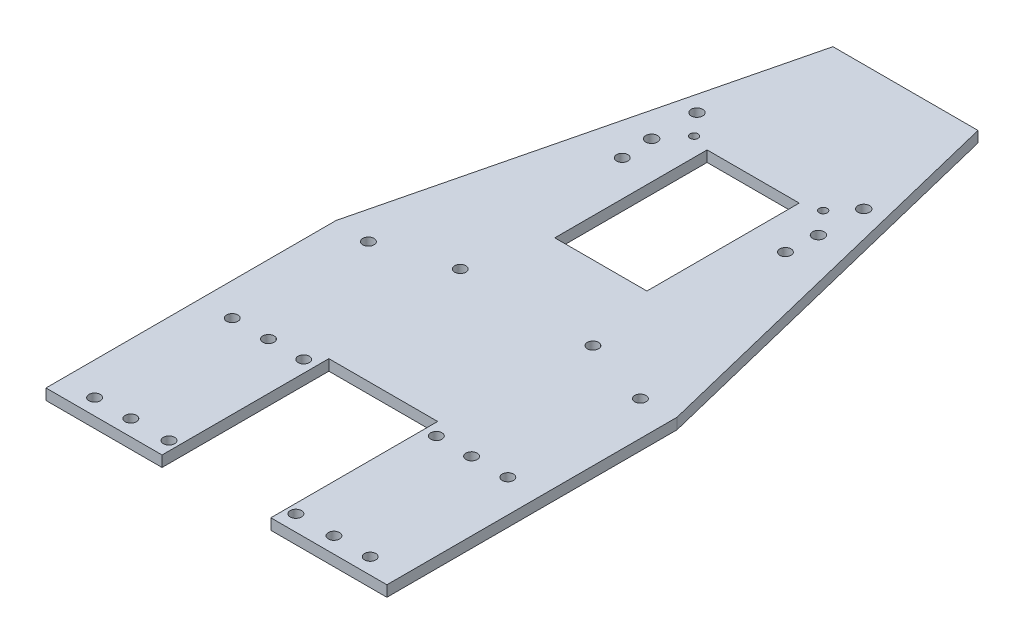
SolidWorks part; units mm, degrees
material "Acrylic (Medium-high impact)"
ref_plane "Front Plane" through (0, 0, 0) normal (0, 0, 1) x (1, 0, 0)
ref_plane "Top Plane" through (0, 0, 0) normal (0, 1, 0) x (1, 0, 0)
ref_plane "Right Plane" through (0, 0, 0) normal (1, 0, 0) x (0, 0, -1)
sketch "Sketch3" plane through (0, 0, 0) normal (0, 1, 0) x (1, 0, 0)
  line L0 (-15, -46) -> (-47, -46)
  line L1 (-47, -46) -> (-47, 34)
  line L2 (-47, 34) -> (-20, 144)
  line L3 (-20, 144) -> (20, 144)
  line L4 (20, 144) -> (47, 34)
  line L5 (47, 34) -> (47, -46)
  line L6 (47, -46) -> (15, -46)
  line L7 (15, -46) -> (15, 0)
  line L8 (15, 0) -> (-15, 0)
  line L9 (-15, 0) -> (-15, -46)
  point P11 (0, 0)
  dimension "D1" = 30
  dimension "D2" = 32
  dimension "D3" = 46
  dimension "D4" = 80
  dimension "D5" = 110
  dimension "D6" = 40
extrude "Body" add sketch "Sketch3" along normal blind 3
sketch "Sketch4" plane through (0, 3, 0) normal (0, 1, 0) x (1, 0, 0)
  line L0 (-47, -3.65) -> (47, -3.65) construction
  line L1 (-47, 34) -> (-47, -46) construction
  line L2 (47, -46) -> (47, 34) construction
  line L3 (-47, -41.6) -> (47, -41.6) construction
  line L5 (-47, -46) -> (-15, -46) construction
  line L6 (0, 0) -> (0, -41.6) construction
  line L8 (-18.29, -3.65) -> (18.29, -3.65) construction
  line L9 (-18.29, -3.65) -> (-18.29, 39.53) construction
  line L10 (-18.29, 39.53) -> (18.29, 39.53) construction
  line L11 (18.29, -3.65) -> (18.29, 39.53) construction
  circle A0 centre (-38, -3.65) radius 1.55
  circle A1 centre (-28, -3.65) radius 1.55
  circle A2 centre (-38, -41.6) radius 1.55
  circle A3 centre (-28, -41.6) radius 1.55
  circle A4 centre (-18.29, -3.65) radius 1.55
  circle A7 centre (18.29, -3.65) radius 1.55
  circle A8 centre (28, -41.6) radius 1.55
  circle A9 centre (38, -41.6) radius 1.55
  circle A10 centre (28, -3.65) radius 1.55
  circle A11 centre (38, -3.65) radius 1.55
  circle A14 centre (-18.29, 39.53) radius 1.55
  circle A15 centre (18.29, 39.53) radius 1.55
  dimension "D3" = 3.1
  dimension "D1" = 42.35
  dimension "D2" = 4.4
  dimension "D4" = 18.29
  dimension "D5" = 28
  dimension "D6" = 38
  dimension "D7" = 43.18
extrude "Motor Mount" cut sketch "Sketch4" against normal blind 3
sketch "Sketch5" plane through (0, 3, 0) normal (0, 1, 0) x (1, 0, 0)
  line L0 (0, 0) -> (0, 60) construction
  line L1 (-12.7, 60) -> (12.7, 60)
  line L2 (-12.7, 60) -> (-12.7, 102)
  line L3 (-12.7, 102) -> (12.7, 102)
  line L4 (12.7, 60) -> (12.7, 102)
  line L5 (-15, 0) -> (15, 0) construction
  line L6 (-17.8, 103.5) -> (17.8, 103.5) construction
  line L7 (0, 103.5) -> (0, 60) construction
  circle A0 centre (-17.8, 103.5) radius 1.1
  circle A1 centre (17.8, 103.5) radius 1.1
  dimension "D4" = 2.2
  dimension "D1" = 25.4
  dimension "D2" = 42
  dimension "D3" = 60
  dimension "D5" = 1.5
  dimension "D6" = 35.6
extrude "Protoboard Mount" cut sketch "Sketch5" against normal blind 10
sketch "Sketch6" plane through (0, 3, 0) normal (0, 1, 0) x (1, 0, 0)
  line L0 (-23, 97) -> (23, 97) construction
  line L1 (0, 97) -> (0, 102) construction
  line L2 (12.7, 102) -> (-12.7, 102) construction
  line L3 (-23, 97) -> (-23, 109.5) construction
  line L4 (23, 97) -> (23, 109.5) construction
  circle A3 centre (-23, 109.5) radius 1.6
  circle A4 centre (-23, 97) radius 1.6
  circle A5 centre (23, 97) radius 1.6
  circle A6 centre (23, 109.5) radius 1.6
  dimension "D2" = 12.5
  dimension "D1" = 46
  dimension "D4" = 3.2
  dimension "D3" = 5
extrude "Caster Mount" cut sketch "Sketch6" against normal blind 10
sketch "Sketch8" plane through (0, 3, 0) normal (0, 1, 0) x (1, 0, 0)
  line L0 (-22.5, 88.4) -> (22.5, 88.4) construction
  line L1 (-37.5, 33.4) -> (37.5, 33.4) construction
  line L2 (-17.5, -41.6) -> (17.5, -41.6) construction
  line L3 (0, 88.4) -> (0, -41.6) construction
  line L4 (-17.5, -41.6) -> (-28, -41.6) construction
  circle A0 centre (-22.5, 88.4) radius 1.55
  circle A1 centre (22.5, 88.4) radius 1.55
  circle A2 centre (37.5, 33.4) radius 1.55
  circle A3 centre (-37.5, 33.4) radius 1.55
  circle A4 centre (-17.5, -41.6) radius 1.55
  circle A5 centre (17.5, -41.6) radius 1.55
  point P14 (0, 33.4)
  dimension "D1" = 3.1
  dimension "D2" = 45
  dimension "D3" = 75
  dimension "D4" = 35
  dimension "D5" = 75
  dimension "D6" = 55
extrude "Stand Off Mount" cut sketch "Sketch8" against normal blind 10
